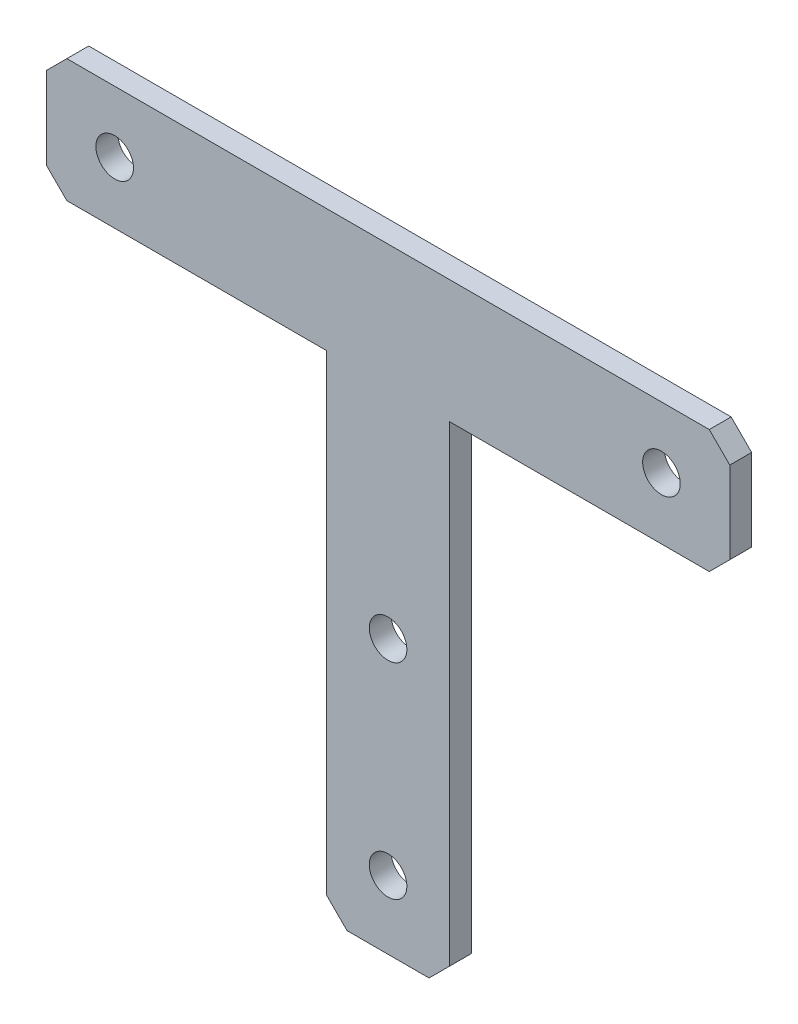
SolidWorks part; units mm, degrees
ref_plane "Front Plane" through (0, 0, 0) normal (0, 0, 1) x (1, 0, 0)
ref_plane "Top Plane" through (0, 0, 0) normal (0, 1, 0) x (1, 0, 0)
ref_plane "Right Plane" through (0, 0, 0) normal (1, 0, 0) x (0, 0, -1)
ref_plane "Plane1" through (0, 0, 0) normal (0, 0, 1) x (1, 0, 0)
sketch "Sketch1" plane through (0, 0, 0) normal (0, 0, 1) x (1, 0, 0)
  line L0 (-50, 75) -> (-47, 72)
  line L1 (-47, 72) -> (-9, 72)
  line L2 (-9, 72) -> (-9, 3)
  line L3 (-9, 3) -> (-6, 0)
  line L4 (-6, 0) -> (6, 0)
  line L5 (6, 0) -> (9, 3)
  line L6 (9, 3) -> (9, 72)
  line L7 (9, 72) -> (47, 72)
  line L8 (47, 72) -> (50, 75)
  line L9 (50, 75) -> (50, 87)
  line L10 (50, 87) -> (47, 90)
  line L11 (47, 90) -> (-47, 90)
  line L12 (-47, 90) -> (-50, 87)
  line L13 (-50, 87) -> (-50, 75)
  circle A0 centre (40, 81) radius 2.75
  circle A1 centre (0, 40) radius 2.75
  circle A2 centre (0, 10) radius 2.75
  circle A3 centre (-40, 81) radius 2.75
extrude "Boss-Extrude1" add sketch "Sketch1" against normal blind 3.2
